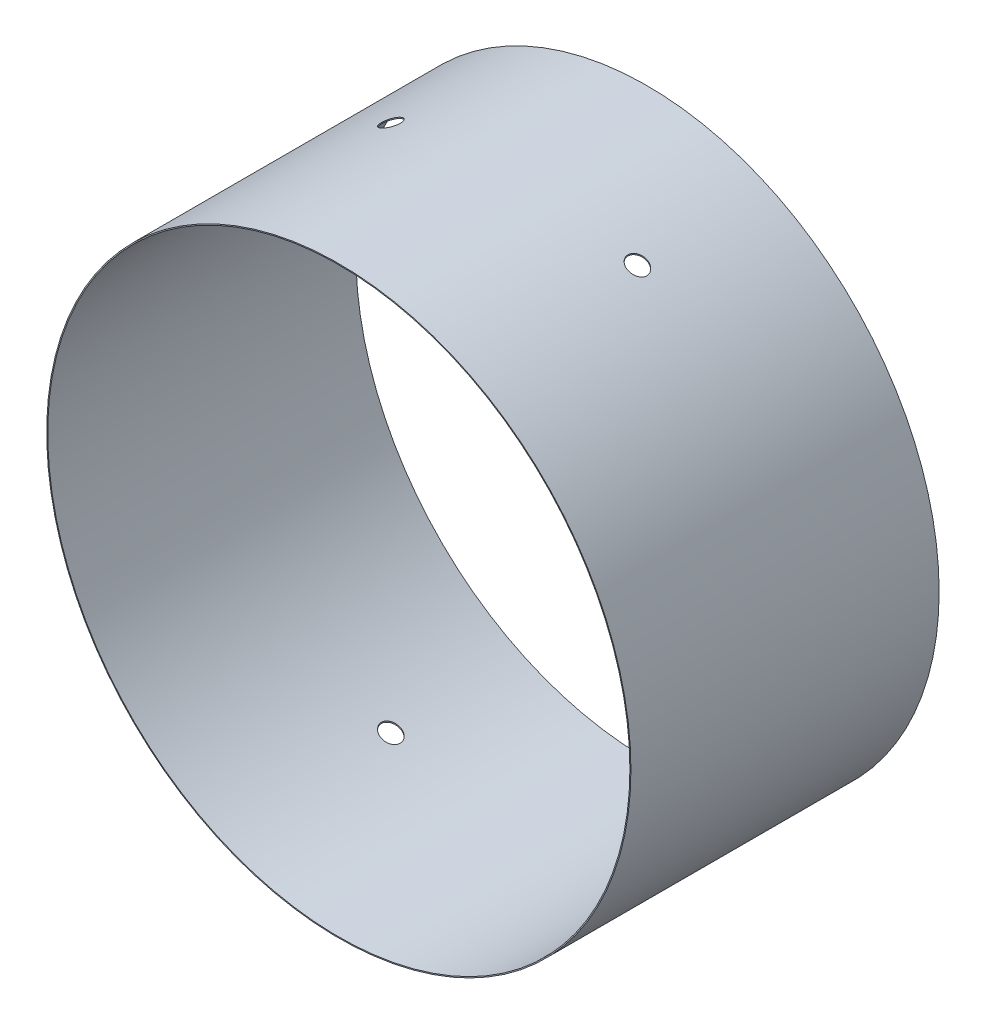
SolidWorks part; units mm, degrees
material "Galvanized Steel"
ref_plane "Front Plane" through (0, 0, 0) normal (0, 0, 1) x (1, 0, 0)
ref_plane "Top Plane" through (0, 0, 0) normal (0, 1, 0) x (1, 0, 0)
ref_plane "Right Plane" through (0, 0, 0) normal (1, 0, 0) x (0, 0, -1)
sketch "Sketch1" plane through (0, 0, 0) normal (0, 0, 1) x (1, 0, 0)
  circle A0 centre (0, 0) radius 425
  circle A1 centre (0, 0) radius 426.5
  dimension "D1" = 850
  dimension "D2" = 1.5
extrude "Boss-Extrude1" add sketch "Sketch1" along normal blind 450
sketch "Sketch2" plane through (0, 0, 0) normal (0, 1, 0) x (1, 0, 0)
  line L0 (0, 0) -> (0, 183.8928) construction
  line L1 (-426.5, -450) -> (426.5, -450) construction
  circle A0 centre (180, -194) radius 13.75
  circle A1 centre (-180, -194) radius 13.75
  dimension "D1" = 27.5
  dimension "D2" = 180
  dimension "D3" = 256
extrude "Cut-Extrude1" cut sketch "Sketch2" against normal through all both and the other way through all
